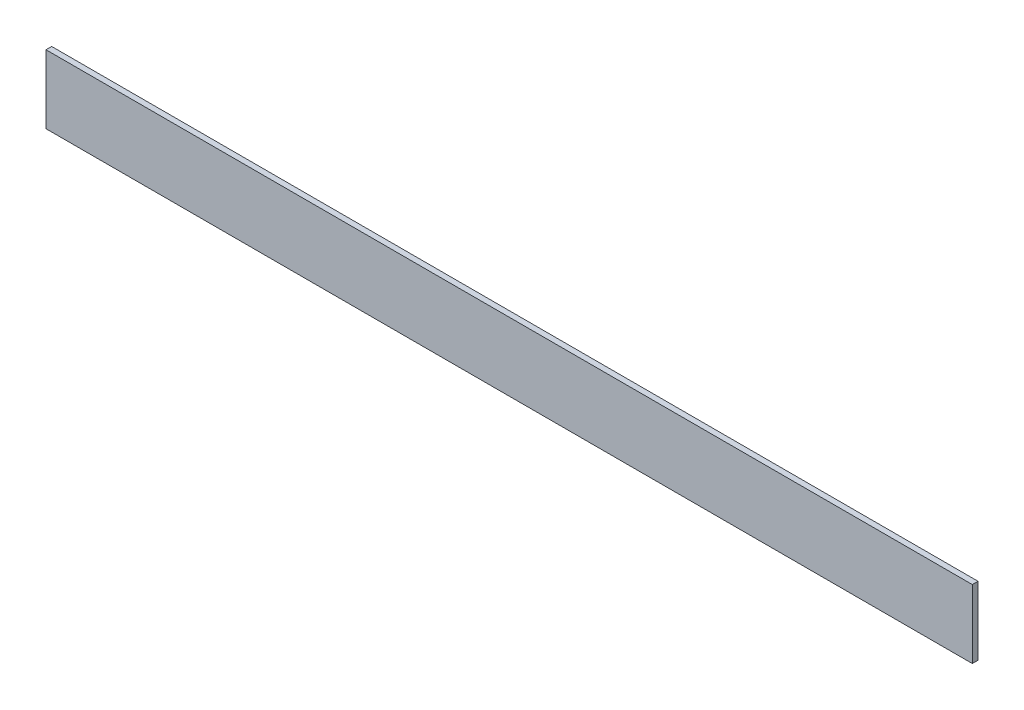
SolidWorks part; units mm, degrees
material "Pine"
ref_plane "Front Plane" through (0, 0, 0) normal (0, 0, 1) x (1, 0, 0)
ref_plane "Top Plane" through (0, 0, 0) normal (0, 1, 0) x (1, 0, 0)
ref_plane "Right Plane" through (0, 0, 0) normal (1, 0, 0) x (0, 0, -1)
sketch "Sketch1" plane through (0, 0, 0) normal (0, 0, 1) x (1, 0, 0)
  line L1 (-515.874, 38.1) -> (515.874, 38.1)
  line L2 (-515.874, 38.1) -> (-515.874, -38.1)
  line L3 (-515.874, -38.1) -> (515.874, -38.1)
  line L4 (515.874, 38.1) -> (515.874, -38.1)
  line L5 (-515.874, 38.1) -> (515.874, -38.1) construction
  line L6 (-515.874, -38.1) -> (515.874, 38.1) construction
  point P0 (0, 0)
  dimension "D1" = 1031.748
extrude "Boss-Extrude1" add sketch "Sketch1" along normal blind 6.35
